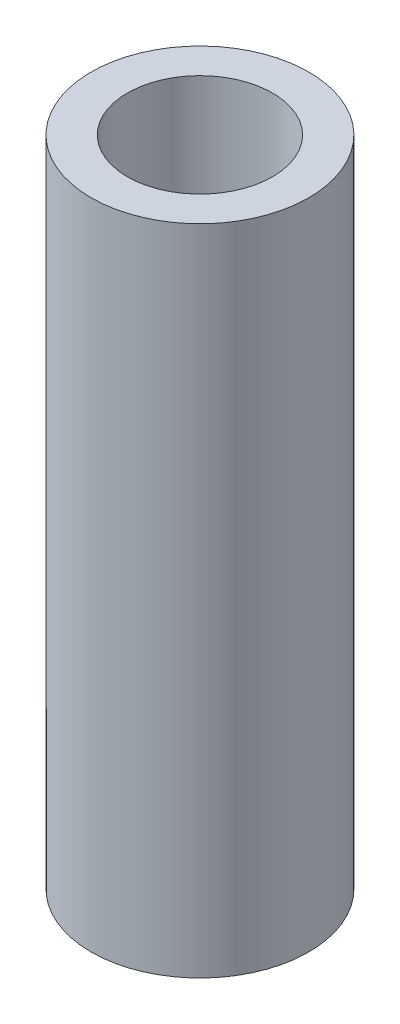
SolidWorks part; units mm, degrees
ref_plane "Front Plane" through (0, 0, 0) normal (0, 0, 1) x (1, 0, 0)
ref_plane "Top Plane" through (0, 0, 0) normal (0, 1, 0) x (1, 0, 0)
ref_plane "Right Plane" through (0, 0, 0) normal (1, 0, 0) x (0, 0, -1)
sketch "Sketch1" plane through (0, 0, 0) normal (0, 1, 0) x (1, 0, 0)
  circle A0 centre (0, 0) radius 3
  dimension "D1" = 6
extrude "Boss-Extrude1" add sketch "Sketch1" along normal blind 18
sketch "Sketch2" plane through (0, 18, 0) normal (0, 1, 0) x (1, 0, 0)
  circle A0 centre (0, 0) radius 2
  dimension "D1" = 4
extrude "Cut-Extrude1" cut sketch "Sketch2" against normal through all
